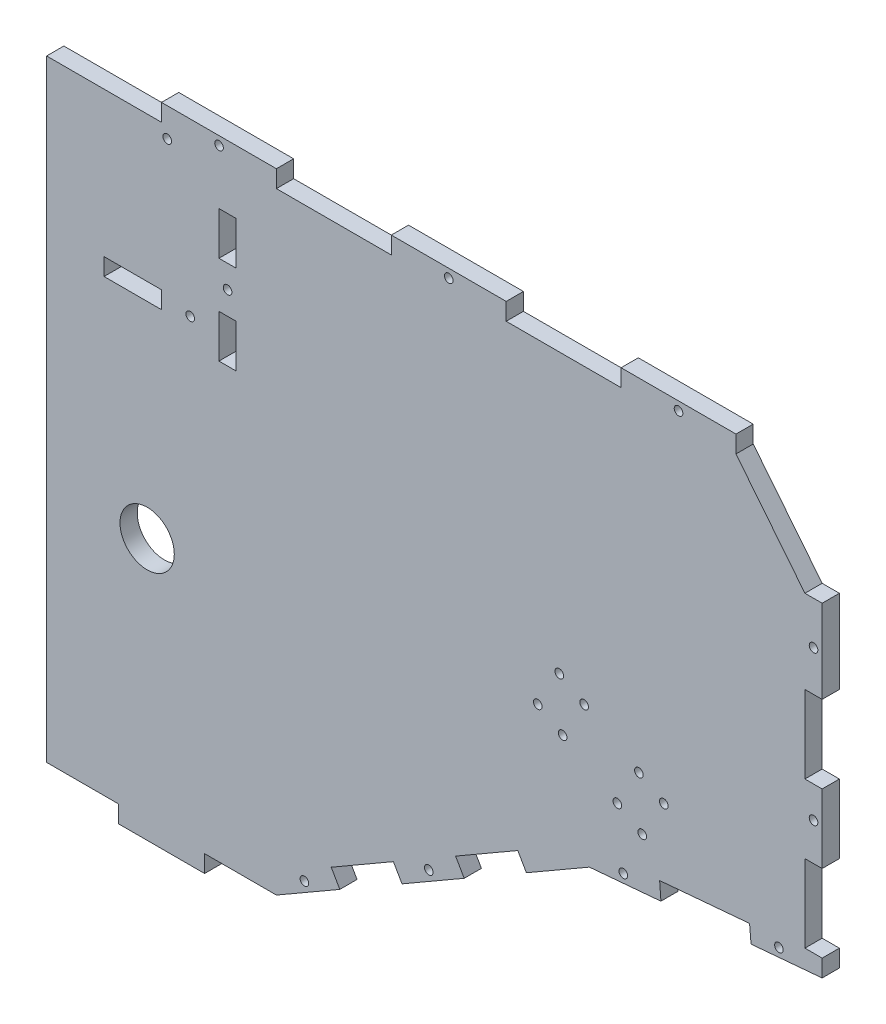
SolidWorks part; units mm, degrees
ref_plane "Plan de face" through (0, 0, 0) normal (0, 0, 1) x (1, 0, 0)
ref_plane "Plan de dessus" through (0, 0, 0) normal (0, 1, 0) x (1, 0, 0)
ref_plane "Plan de droite" through (0, 0, 0) normal (1, 0, 0) x (0, 0, -1)
sketch "Esquisse1" plane through (0, 0, 0) normal (0, 0, 1) x (1, 0, 0)
  line L1 (135, -106.5) -> (-135, -106.5)
  line L2 (135, -106.5) -> (135, 106.5)
  line L3 (135, 106.5) -> (-135, 106.5)
  line L4 (-135, -106.5) -> (-135, 106.5)
  line L5 (135, -106.5) -> (-135, 106.5) construction
  line L6 (135, 106.5) -> (-135, -106.5) construction
  point P0 (0, 0)
  dimension "D1" = 270
  dimension "D2" = 213
extrude "Boss.-Extru.1" add sketch "Esquisse1" along normal blind 6
sketch "Esquisse3" plane through (0, 0, 6) normal (0, 0, 1) x (1, 0, 0)
  line L0 (-135, -106.5) -> (135, -106.5) construction
  line L1 (-135, 106.5) -> (-135, -106.5) construction
  line L2 (-135, -106.5) -> (135, -106.5) construction
  line L3 (-135, 106.5) -> (-135, -106.5) construction
  circle A0 centre (-100, -21.5) radius 9.45
  circle A1 centre (43.4897, 9.5237) radius 1.5
  circle A2 centre (52.1499, 4.5237) radius 1.5
  circle A3 centre (35.9897, -3.4667) radius 1.5
  circle A4 centre (44.6499, -8.4667) radius 1.5
  circle A5 centre (63.7025, -19.4667) radius 1.5
  circle A6 centre (72.3627, -24.4667) radius 1.5
  circle A7 centre (79.8627, -11.4763) radius 1.5
  circle A8 centre (71.2025, -6.4763) radius 1.5
  dimension "D1" = 85
  dimension "D3" = 3
  dimension "D4" = 3
  dimension "D5" = 3
  dimension "D6" = 3
  dimension "D7" = 3
  dimension "D8" = 3
  dimension "D9" = 3
  dimension "D10" = 3
  dimension "D11" = 82.0333
  dimension "D12" = 3
  dimension "D13" = 18.9
  dimension "D14" = 8.6603
  dimension "D15" = 19.0526
  dimension "D16" = 12.9904
  dimension "D17" = 170.9897
  dimension "D18" = 103.0333
  dimension "D19" = 7.5
  dimension "D20" = 8.6603
  dimension "D21" = 7.5
  dimension "D22" = 11
  dimension "D2" = 35
extrude "Enlèv. mat.-Extru.1" cut sketch "Esquisse3" against normal blind 10
sketch "Esquisse5" plane through (0, 0, 6) normal (0, 0, 1) x (1, 0, 0)
  line L0 (53.9637, -43.5898) -> (135, -36.5)
  line L1 (53.9637, -43.5898) -> (-55, -106.5)
  line L3 (135, -106.5) -> (135, 106.5) construction
  line L4 (-135, -106.5) -> (135, -106.5) construction
  dimension "D1" = 80
  dimension "D2" = 95
  dimension "D3" = 0
  dimension "D4" = 150
  dimension "D5" = 70
  dimension "D6" = 0
extrude "Enlèv. mat.-Extru.11" cut sketch "Esquisse5" against normal through all and the other way through all
sketch "Esquisse6" plane through (0, 106.5, 0) normal (0, 1, 0) x (1, 0, 0)
  line L0 (135, -6) -> (-135, -6) construction
  line L1 (-55, -6) -> (-95, -6)
  line L2 (-55, -6) -> (-55, 0)
  line L3 (-55, 0) -> (-95, 0)
  line L4 (-95, -6) -> (-95, 0)
  line L5 (135, 0) -> (-135, 0) construction
  line L7 (-15, -6) -> (25, -6)
  line L8 (-15, -6) -> (-15, 0)
  line L9 (-15, 0) -> (25, 0)
  line L10 (25, -6) -> (25, 0)
  line L11 (105, -6) -> (65, -6)
  line L12 (105, -6) -> (105, 0)
  line L13 (105, 0) -> (65, 0)
  line L14 (65, -6) -> (65, 0)
  dimension "D1" = 40
  dimension "D2" = 40
  dimension "D3" = 40
  dimension "D4" = 40
  dimension "D5" = 40
  dimension "D6" = 40
extrude "Boss.-Extru.2" add sketch "Esquisse6" along normal blind 6
sketch "Esquisse7" plane through (0, 0, 0) normal (0, 0, -1) x (-1, 0, 0)
  line L1 (-135, -36.5) -> (-135, 106.5) construction
  line L2 (-135, 106.5) -> (-129, 106.5)
  line L3 (-135, 106.5) -> (-135, 76.5)
  line L4 (-135, 76.5) -> (-129, 76.5)
  line L6 (-129, 106.5) -> (-129, 76.5)
  line L7 (-135, 47.5) -> (-129, 47.5)
  line L8 (-135, 47.5) -> (-135, 20.5)
  line L9 (-135, 20.5) -> (-129, 20.5)
  line L10 (-129, 47.5) -> (-129, 20.5)
  line L12 (-135, -3.5) -> (-129, -3.5)
  line L13 (-135, -3.5) -> (-135, -30.5)
  line L14 (-135, -30.5) -> (-129, -30.5)
  line L15 (-129, -3.5) -> (-129, -30.5)
  dimension "D1" = 6
  dimension "D2" = 30
  dimension "D3" = 29
  dimension "D4" = 6
  dimension "D5" = 6
  dimension "D6" = 27
  dimension "D7" = 24
  dimension "D8" = 27
extrude "Enlèv. mat.-Extru.12" cut sketch "Esquisse7" against normal blind 6
sketch "Esquisse8" plane through (0, -106.5, 0) normal (0, -1, 0) x (1, 0, 0)
  line L0 (-135, 0) -> (-55, 0) construction
  line L1 (-80, 0) -> (-110, 0)
  line L2 (-80, 0) -> (-80, 6)
  line L3 (-80, 6) -> (-110, 6)
  line L4 (-110, 0) -> (-110, 6)
  line L5 (-135, 6) -> (-55, 6) construction
  dimension "D1" = 30
  dimension "D2" = 25
extrude "Boss.-Extru.3" add sketch "Esquisse8" along normal blind 6
sketch "Esquisse9" plane through (0, 0, 0) normal (0, 0, -1) x (-1, 0, 0)
  line L0 (-110.25, -38.6653) -> (-109.7271, -32.6882)
  line L1 (-53.9637, -43.5898) -> (-135, -36.5) construction
  line L3 (-78.8637, -41.4113) -> (-78.423, -35.4113)
  line L4 (-78.423, -35.4113) -> (-109.7271, -32.6882)
  line L5 (-110.25, -38.6653) -> (-78.8637, -41.4113)
  dimension "D1" = 90
  dimension "D2" = 6
  dimension "D3" = 24.9
  dimension "D4" = 24.75
  dimension "D5" = 6
extrude "Enlèv. mat.-Extru.13" cut sketch "Esquisse9" against normal through all
sketch "Esquisse10" plane through (0, 0, 0) normal (0, 0, -1) x (-1, 0, 0)
  line L0 (-32.0356, -56.25) -> (-10.3849, -68.75)
  line L1 (55, -106.5) -> (-53.9637, -43.5898) construction
  line L2 (-10.3849, -68.75) -> (-7.3849, -63.5538)
  line L3 (-7.3849, -63.5538) -> (-29.0356, -51.0538)
  line L4 (-29.0356, -51.0538) -> (-32.0356, -56.25)
  line L5 (11.2657, -81.25) -> (32.9164, -93.75)
  line L6 (32.9164, -93.75) -> (35.9164, -88.5538)
  line L7 (35.9164, -88.5538) -> (14.2657, -76.0538)
  line L8 (14.2657, -76.0538) -> (11.2657, -81.25)
  dimension "D1" = 6
  dimension "D2" = 6
  dimension "D3" = 25
  dimension "D4" = 25
  dimension "D5" = 25
  dimension "D6" = 25.5
extrude "Enlèv. mat.-Extru.14" cut sketch "Esquisse10" against normal blind 10
sketch "Esquisse11" plane through (0, 0, 0) normal (0, 0, -1) x (-1, 0, 0)
  line L0 (135, 106.5) -> (135, -106.5) construction
  line L1 (69, 59.5) -> (75, 59.5)
  line L2 (69, 59.5) -> (69, 44.5)
  line L3 (69, 44.5) -> (75, 44.5)
  line L4 (75, 59.5) -> (75, 44.5)
  line L5 (80, -106.5) -> (55, -106.5) construction
  line L7 (69, 90.5) -> (75, 90.5)
  line L8 (69, 90.5) -> (69, 75.5)
  line L9 (69, 75.5) -> (75, 75.5)
  line L10 (75, 90.5) -> (75, 75.5)
  dimension "D1" = 15
  dimension "D2" = 6
  dimension "D3" = 60
  dimension "D4" = 151
  dimension "D5" = 15
  dimension "D6" = 16
extrude "Enlèv. mat.-Extru.15" cut sketch "Esquisse11" against normal through all
sketch "Esquisse13" plane through (0, 0, 0) normal (0, 0, -1) x (-1, 0, 0)
  line L0 (-129, 76.5) -> (-129, 106.5)
  line L1 (-129, 106.5) -> (-105, 106.5)
  line L2 (-105, 106.5) -> (-129, 76.5)
extrude "Enlèv. mat.-Extru.17" cut sketch "Esquisse13" against normal through all
sketch "Esquisse15" plane through (0, 0, 0) normal (0, 0, -1) x (-1, 0, 0)
  line L0 (-105, 112.5) -> (-65, 112.5) construction
  line L1 (14.2657, -76.0538) -> (11.2657, -81.25) construction
  line L2 (-25, 112.5) -> (-25, 106.5) construction
  line L3 (55, 112.5) -> (55, 106.5) construction
  line L4 (-135, -3.5) -> (-135, 20.5) construction
  line L5 (-135, 47.5) -> (-135, 76.5) construction
  line L6 (-53.9637, -43.5898) -> (-78.8637, -41.4113) construction
  line L7 (11.2657, -81.25) -> (-10.3849, -68.75) construction
  line L8 (55, -106.5) -> (32.9164, -93.75) construction
  line L9 (69, 75.5) -> (75, 75.5) construction
  line L10 (-78.8637, -41.4113) -> (-78.423, -35.4113) construction
  line L11 (35.9164, -88.5538) -> (32.9164, -93.75) construction
  line L12 (-110.25, -38.6653) -> (-135, -36.5) construction
  line L13 (-109.7271, -32.6882) -> (-110.25, -38.6653) construction
  line L14 (69, 90.5) -> (69, 75.5) construction
  line L15 (75, 59.5) -> (69, 59.5) construction
  line L16 (75, 44.5) -> (75, 59.5) construction
  circle A0 centre (-85, 109.5) radius 2.995
  circle A1 centre (-5, 109.5) radius 2.995
  circle A2 centre (75, 109.5) radius 2.995
  circle A3 centre (1.9404, -72.4019) radius 2.995
  circle A4 centre (-65.7671, -39.571) radius 2.995
  circle A5 centre (45.2417, -97.4019) radius 2.95
  circle A6 centre (-132, 9.5511) radius 2.995
  circle A7 centre (-132, 61.5795) radius 2.995
  circle A8 centre (-119.9505, -34.8052) radius 2.995
  circle A9 centre (72, 67.5) radius 3
  circle A10 centre (85, 53) radius 3
  point P8 (55, 109.5)
  point P10 (-25, 109.5)
  point P29 (-66.4137, -42.5005)
  point P42 (12.7657, -78.6519)
  dimension "D1" = 3
  dimension "D2" = 5.99
  dimension "D3" = 5.99
  dimension "D4" = 5.99
  dimension "D8" = 5.99
  dimension "D9" = 5.99
  dimension "D13" = 5.99
  dimension "D14" = 5.99
  dimension "D16" = 5.9
  dimension "D21" = 5.99
  dimension "D24" = 8
  dimension "D25" = 6
  dimension "D26" = 3
  dimension "D27" = 6
  dimension "D28" = 6.5
  dimension "D29" = 10
  dimension "D5" = 20
  dimension "D6" = 20
  dimension "D7" = 20
  dimension "D10" = 3
  dimension "D11" = 3
  dimension "D12" = 3
  dimension "D15" = 3
  dimension "D17" = 3
  dimension "D18" = 12.9266
  dimension "D19" = 12.5
  dimension "D20" = 12.5
  dimension "D22" = 3
  dimension "D23" = 10
extrude "Enlèv. mat.-Extru.19" cut sketch "Esquisse15" against normal blind 3
sketch "Esquisse16" plane through (0, 0, 0) normal (0, 0, -1) x (-1, 0, 0)
  line L0 (69, 90.5) -> (69, 75.5) construction
  line L2 (69, 75.5) -> (75, 75.5) construction
  line L3 (75, 44.5) -> (75, 59.5) construction
  line L4 (75, 59.5) -> (69, 59.5) construction
  line L5 (55, 112.5) -> (95, 112.5) construction
  line L6 (135, 106.5) -> (135, -106.5) construction
  circle A0 centre (-5, 109.5) radius 1.5
  circle A1 centre (74.9678, 109.5) radius 1.5
  circle A2 centre (-85, 109.5) radius 1.5
  circle A3 centre (-132, 61.5795) radius 1.5
  circle A4 centre (-132, 9.5511) radius 1.5
  circle A5 centre (-119.9505, -34.8052) radius 1.5
  circle A6 centre (-65.7671, -39.571) radius 1.5
  circle A7 centre (1.9404, -72.4019) radius 1.5
  circle A8 centre (45.2417, -97.4019) radius 1.5
  circle A9 centre (72, 67.5) radius 1.5
  circle A10 centre (85, 53) radius 1.5
  circle A11 centre (93, 102.5) radius 1.5
  dimension "D1" = 3
  dimension "D2" = 3
  dimension "D3" = 8
  dimension "D4" = 3
  dimension "D5" = 10
  dimension "D6" = 6.5
  dimension "D7" = 3
  dimension "D8" = 10
  dimension "D9" = 42
extrude "Enlèv. mat.-Extru.20" cut sketch "Esquisse16" against normal blind 10
sketch "Esquisse17" plane through (0, 0, 0) normal (0, 0, -1) x (-1, 0, 0)
  line L0 (-105, 112.5) -> (-65, 112.5) construction
  line L1 (95, 56) -> (115, 56)
  line L2 (95, 56) -> (95, 50)
  line L3 (95, 50) -> (115, 50)
  line L4 (115, 56) -> (115, 50)
  line L6 (135, 106.5) -> (135, -106.5) construction
  dimension "D1" = 6
  dimension "D2" = 20
  dimension "D3" = 56.5
  dimension "D4" = 20
extrude "Enlèv. mat.-Extru.22" cut sketch "Esquisse17" against normal blind 10
